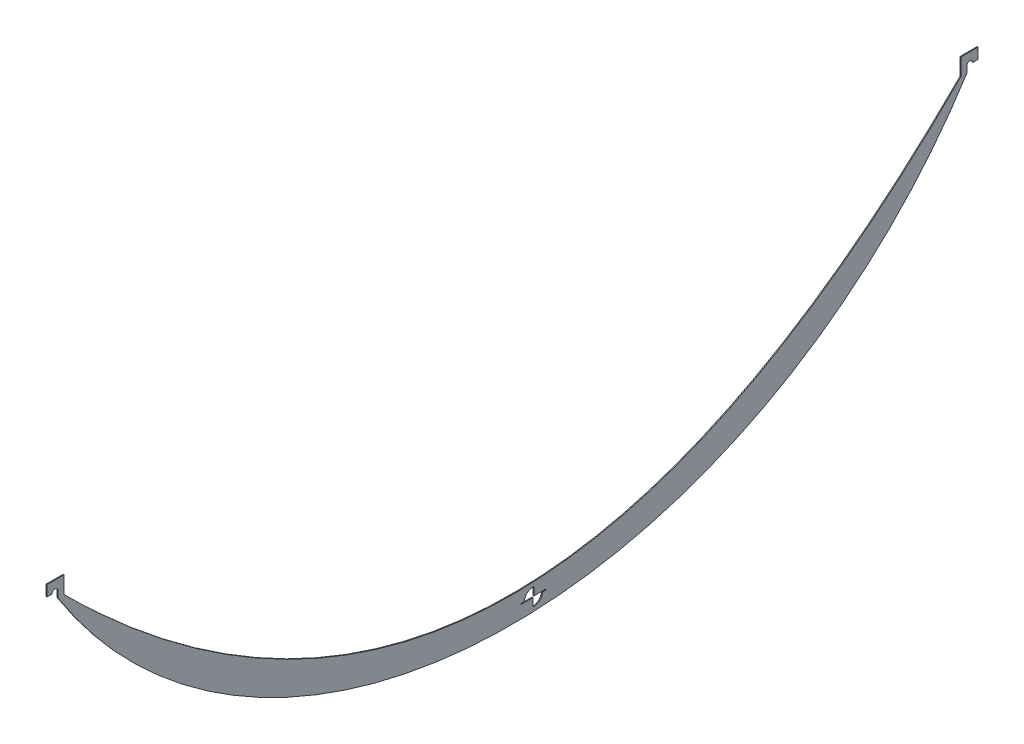
SolidWorks part; units mm, degrees
material "6061 Alloy"
ref_plane "Front Plane" through (0, 0, 0) normal (0, 0, 1) x (1, 0, 0)
ref_plane "Top Plane" through (0, 0, 0) normal (0, 1, 0) x (1, 0, 0)
ref_plane "Right Plane" through (0, 0, 0) normal (1, 0, 0) x (0, 0, -1)
sketch "Sketch60" plane through (0, 0, 0) normal (1, 0, 0) x (0, 0, -1)
  line L0 (-1327.15, 331.7875) -> (1327.15, 331.7875) construction
  line L1 (0, 331.7875) -> (0, -331.7875) construction
  line L2 (1345.0824, 331.7875) -> (1345.0824, 359.7273) construction
  line L3 (1345.0824, 359.7273) -> (1372.7699, 359.7273) construction
  line L5 (1327.15, 331.7875) -> (1327.15, 382.5874)
  line L6 (1327.15, 382.5874) -> (1377.95, 382.5874)
  line L7 (1377.95, 382.5874) -> (1377.95, 350.7612)
  line L8 (1377.95, 350.7612) -> (1363.0148, 350.7612)
  line L9 (1345.0824, 350.7612) -> (1345.0824, 331.7875)
  line L10 (-1345.0824, 359.7273) -> (-1372.7699, 359.7273) construction
  line L11 (-1345.0824, 331.7875) -> (-1345.0824, 359.7273) construction
  line L12 (-1345.0824, 350.7612) -> (-1345.0824, 331.7875)
  line L13 (-1377.95, 350.7612) -> (-1363.0148, 350.7612)
  line L14 (-1377.95, 382.5874) -> (-1377.95, 350.7612)
  line L15 (-1327.15, 382.5874) -> (-1377.95, 382.5874)
  line L16 (-1327.15, 331.7875) -> (-1327.15, 382.5874)
  line L18 (0, -331.7875) -> (0, -407.9548) construction
  arc A0 (1363.0148, 350.7612) -> (1345.0824, 350.7612) centre (1354.0486, 350.7612) ccw
  arc A1 (-1363.0148, 350.7612) -> (-1345.0824, 350.7612) centre (-1354.0486, 350.7612) cw
  arc A2 (1345.0824, 331.7875) -> (-1345.0824, 331.7875) centre (0, 1184.8062) cw
  parabola Q2 (1327.15, 331.7875) -> (-1327.15, 331.7875) focus (0, 331.7875) apex (0, -331.7875)
  dimension "D3" = 76.1673
  dimension "D1" = 2654.3
  dimension "D2" = 663.575
extrude "Boss-Extrude1" add sketch "Sketch60" along normal blind 2.54
sketch "Sketch61" plane through (2.54, 0, 0) normal (1, 0, 0) x (0, 0, -1)
  line L0 (0, -407.9548) -> (0, -264.7545) construction
  line L1 (25.1801, -368.4025) -> (98.8401, -368.4025) construction
  line L2 (62.0101, -343.0025) -> (62.0101, -393.8025) construction
  line L3 (63.2801, -343.0025) -> (63.2801, -367.1325)
  line L4 (63.2801, -393.8025) -> (60.7401, -393.8025)
  line L5 (60.7401, -393.8025) -> (60.7401, -369.6725)
  line L6 (60.7401, -343.0025) -> (63.2801, -343.0025)
  line L7 (98.8401, -369.6725) -> (98.8401, -367.1325)
  line L8 (98.8401, -367.1325) -> (63.2801, -367.1325)
  line L9 (25.1801, -367.1325) -> (25.1801, -369.6725)
  line L10 (88.6801, -369.6725) -> (98.8401, -369.6725)
  line L11 (35.3401, -367.1325) -> (25.1801, -367.1325)
  line L12 (25.1801, -367.1325) -> (25.2335, -367.1573)
  line L13 (60.7401, -369.6725) -> (25.1801, -369.6725)
  arc A0 (-1345.0824, 331.7875) -> (1345.0824, 331.7875) centre (0, 1184.8062) ccw construction
  arc A1 (63.2801, -393.8025) -> (88.6801, -369.6725) centre (63.3119, -368.4025) ccw
  arc A2 (60.7401, -343.0025) -> (35.3401, -367.1325) centre (60.7083, -368.4025) ccw
  circle A3 centre (62.0101, -368.4025) radius 0.6176
  point P12 (62.0101, -368.4025)
  point P13 (62.0101, -368.4025)
  point P16 (62.0101, -343.0025)
  point P21 (98.8401, -368.4025)
  point P24 (63.2801, -369.6725)
  point P25 (63.2801, -369.6725)
  dimension "D1" = 2.54
  dimension "D3" = 25.4
  dimension "D4" = 10.16
  dimension "D2" = 2.54
extrude "Cut-Extrude1" cut sketch "Sketch61" against normal through all contours L9 L13 L5 L4 A1 L10 L7 L8 L3 L6 A2 L11
sketch "Sketch67" plane through (2.54, 0, 0) normal (1, 0, 0) x (0, 0, -1)
  line L0 (63.2801, -367.1325) -> (60.7401, -369.6725) construction
  point P4 (62.0101, -368.4025)
ref_plane "Plane5" through (0, -368.4025, 0) normal (0, 1, 0) x (1, 0, 0)
sketch "Sketch68" plane through (0, -368.4025, 0) normal (0, 1, 0) x (1, 0, 0)
  line L0 (2.54, 62.0101) -> (62.1738, 62.0101) construction
